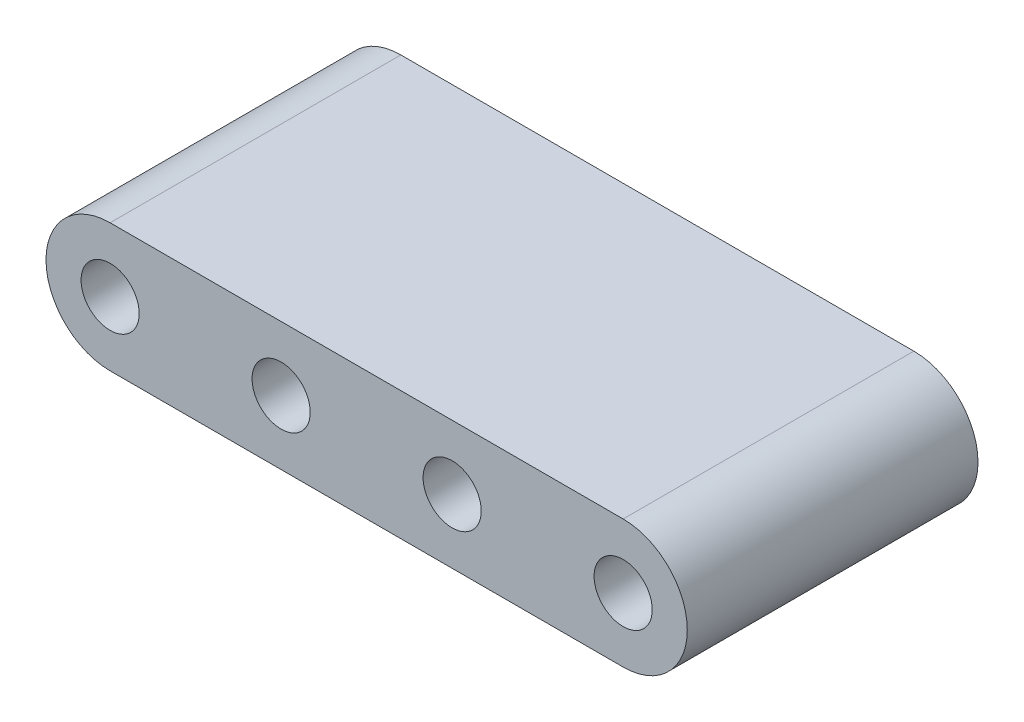
SolidWorks part; units mm, degrees
ref_plane "前视基准面" through (0, 0, 0) normal (0, 0, 1) x (1, 0, 0)
ref_plane "上视基准面" through (0, 0, 0) normal (0, 1, 0) x (1, 0, 0)
ref_plane "右视基准面" through (0, 0, 0) normal (1, 0, 0) x (0, 0, -1)
other "Configuration Table"
sketch "草图1" plane through (0, 0, 0) normal (0, 0, 1) x (1, 0, 0)
  line L0 (0, 0) -> (60, 0) construction
  line L1 (0, 7.5) -> (60, 7.5)
  line L2 (0, -7.5) -> (60, -7.5)
  arc A0 (0, 7.5) -> (0, -7.5) centre (0, 0) ccw
  arc A1 (60, -7.5) -> (60, 7.5) centre (60, 0) ccw
  circle A2 centre (0, 0) radius 3.4
  circle A4 centre (20, 0) radius 3.4
  circle A5 centre (40, 0) radius 3.4
  circle A6 centre (60, 0) radius 3.4
  point P3 (30, 0)
  dimension "D1" = 7.5
  dimension "D2" = 6.8
  dimension "D3" = 60
  dimension "D4" = 4
extrude "凸台-拉伸1" add sketch "草图1" along normal blind 34
move or copy body "实体-移动/复制1" [suppressed] bodies to move or copy 112 parameters "D1"=0, "D2"=0, "D3"=0
move or copy body "实体-移动/复制2" [suppressed] bodies to move or copy 113 parameters "D1"=0, "D2"=0, "D3"=0
